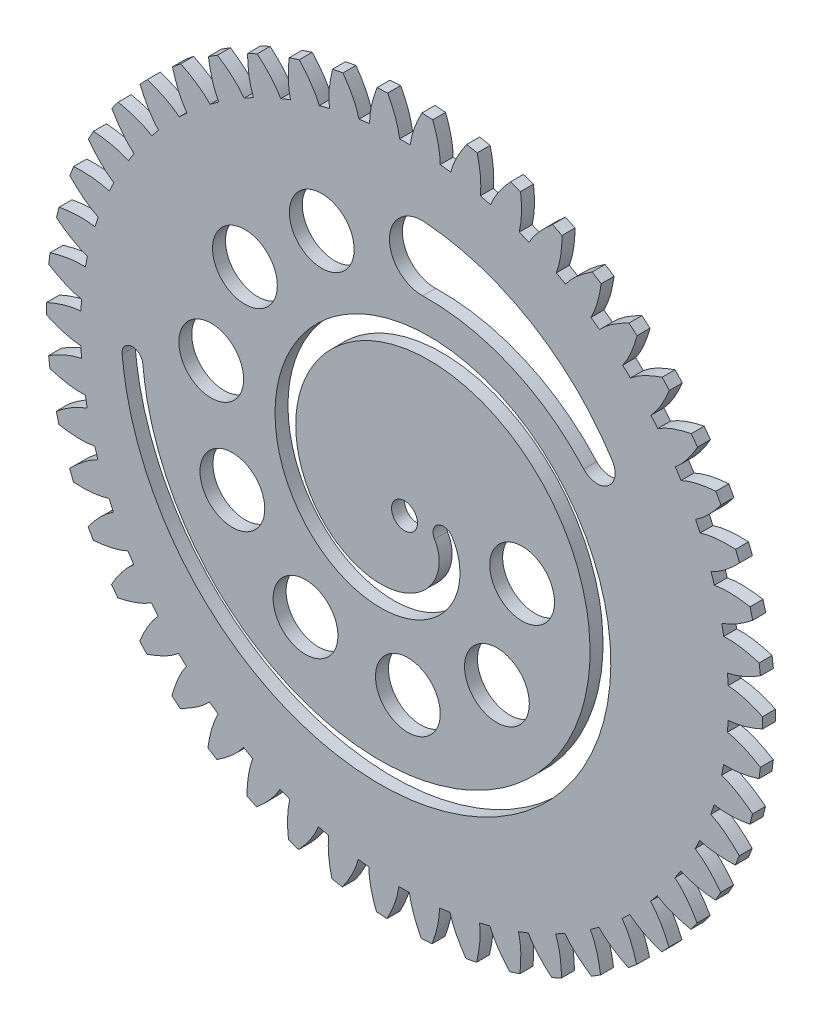
SolidWorks part; units mm, degrees
ref_plane "Front Plane" through (0, 0, 0) normal (0, 0, 1) x (1, 0, 0)
ref_plane "Top Plane" through (0, 0, 0) normal (0, 1, 0) x (1, 0, 0)
ref_plane "Right Plane" through (0, 0, 0) normal (1, 0, 0) x (0, 0, -1)
curve "spiralPointCurve"
  spline degree 3 poles (19.05, 0, 0) (19.4172, -0.6253, 0) (20.1672, -1.9024, 0) (21.0079, -4.0149, 0) (21.6393, -6.2921, 0) (22.0133, -8.7233, 0) (22.1141, -11.2761, 0) (21.9202, -13.9209, 0) (21.4165, -16.6238, 0) (20.5907, -19.3491, 0) (19.4346, -22.0596, 0) (17.9445, -24.7166, 0) (16.1209, -27.2807, 0) (13.9688, -29.7123, 0) (11.4979, -31.9717, 0) (8.7223, -34.0202, 0) (5.6607, -35.8203, 0) (2.3361, -37.3361, 0) (-1.2241, -38.534, 0) (-4.9887, -39.3831, 0) (-8.9227, -39.8555, 0) (-12.9877, -39.9272, 0) (-17.1422, -39.578, 0) (-21.3422, -38.7918, 0) (-25.5415, -37.5576, 0) (-29.6922, -35.8689, 0) (-33.7454, -33.7246, 0) (-37.6513, -31.1285, 0) (-41.3602, -28.0903, 0) (-44.8231, -24.6245, 0) (-47.992, -20.7514, 0) (-50.8203, -16.4964, 0) (-53.2642, -11.8901, 0) (-55.2822, -6.9681, 0) (-56.8365, -1.7705, 0) (-57.8932, 3.6581, 0) (-58.4224, 9.2692, 0) (-58.3993, 15.0108, 0) (-57.8043, 20.8278, 0) (-56.6233, 26.6626, 0) (-54.8479, 32.4557, 0) (-52.476, 38.1461, 0) (-49.5118, 43.6721, 0) (-45.9656, 48.9722, 0) (-41.8544, 53.985, 0) (-37.2014, 58.6506, 0) (-32.0364, 62.9111, 0) (-26.395, 66.711, 0) (-20.3191, 69.9981, 0) (-13.856, 72.7239, 0) (-7.0582, 74.8446, 0) (0.0167, 76.3213, 0) (7.3068, 77.1205, 0) (14.7466, 77.2149, 0) (22.267, 76.5835, 0) (29.7967, 75.2123, 0) (37.2623, 73.0942, 0) (44.589, 70.2296, 0) (51.7019, 66.6261, 0) (58.526, 62.2992, 0) (64.9877, 57.2718, 0) (71.0151, 51.5745, 0) (76.5387, 45.2451, 0) (81.4927, 38.3287, 0) (85.815, 30.8772, 0) (89.4486, 22.9489, 0) (92.3418, 14.6082, 0) (94.4491, 5.9251, 0) (95.7316, -3.0256, 0) (96.1576, -12.1648, 0) (95.7031, -21.4098, 0) (94.3521, -30.6749, 0) (92.0971, -39.8727, 0) (88.939, -48.9143, 0) (84.8878, -57.7105, 0) (79.9619, -66.1726, 0) (74.189, -74.2134, 0) (67.6053, -81.7478, 0) (60.2554, -88.694, 0) (52.1926, -94.9739, 0) (43.4777, -100.5147, 0) (34.1792, -105.2488, 0) (24.3724, -109.1154, 0) (14.139, -112.0603, 0) (3.5664, -114.0377, 0) (-7.2532, -115.0096, 0) (-18.2235, -114.9471, 0) (-29.2447, -113.8307, 0) (-40.2151, -111.6503, 0) (-51.0312, -108.4059, 0) (-61.5893, -104.1076, 0) (-71.7862, -98.7755, 0) (-81.5202, -92.4401, 0) (-90.6922, -85.1417, 0) (-99.2067, -76.9305, 0) (-106.9726, -67.8662, 0) (-113.9048, -58.0177, 0) (-119.9223, -47.4621, 0) (-124.9605, -36.2854, 0) (-128.9275, -24.5778, 0) (-131.8742, -12.448, 0) (-132.8567, -4.1612, 0) (-133.35, 0, 0) knots 0 0 0 0 0.002979 0.006084 0.009318 0.012682 0.016177 0.019804 0.023566 0.027462 0.031493 0.035662 0.039967 0.04441 0.048992 0.053713 0.058573 0.063573 0.068714 0.073995 0.079418 0.084982 0.090688 0.096536 0.102526 0.10866 0.114935 0.121354 0.127917 0.134623 0.141472 0.148465 0.155602 0.162884 0.170309 0.177879 0.185593 0.193453 0.201456 0.209605 0.217898 0.226337 0.234921 0.24365 0.252524 0.261543 0.270708 0.280019 0.289475 0.299076 0.308824 0.318717 0.328756 0.33894 0.349271 0.359748 0.37037 0.381139 0.392054 0.403114 0.414322 0.425675 0.437174 0.44882 0.460612 0.47255 0.484635 0.496866 0.509244 0.521768 0.534439 0.547256 0.560219 0.57333 0.586586 0.59999 0.61354 0.627237 0.64108 0.65507 0.669207 0.68349 0.697921 0.712498 0.727221 0.742092 0.75711 0.772274 0.787585 0.803043 0.818648 0.8344 0.850299 0.866344 0.882537 0.898876 0.915363 0.931996 0.948777 0.965704 0.982779 1 1 1 1
sketch "spiralSketch" plane through (0, 0, 0) normal (0, 0, 1) x (1, 0, 0)
  line L0 (30.4685, 172.8151) -> (35.6087, 171.8296)
  line L1 (8.5687, 175.2711) -> (13.7919, 174.9376)
  line L2 (51.8877, 167.6337) -> (56.8638, 166.0117)
  line L3 (72.4886, 159.8086) -> (77.2222, 157.5757)
  line L4 (91.9463, 149.4632) -> (96.3628, 146.6547)
  line L5 (109.954, 136.7607) -> (113.9836, 133.4208)
  line L6 (126.2277, 121.9014) -> (129.8069, 118.0828)
  line L7 (140.5106, 105.1197) -> (143.583, 100.8826)
  line L8 (152.5776, 86.6801) -> (155.0948, 82.0914)
  line L9 (162.2384, 66.8736) -> (164.1606, 62.0055)
  line L10 (169.3406, 46.0124) -> (170.6375, 40.9418)
  line L11 (173.7722, 24.4256) -> (174.4233, 19.2324)
  line L12 (175.4633, 2.4535) -> (175.4584, -2.7803)
  line L13 (174.3872, -19.5572) -> (173.7264, -24.7491)
  line L14 (170.5609, -41.2595) -> (169.2546, -46.3277)
  line L15 (164.0448, -62.3111) -> (162.1136, -67.1756)
  line L16 (154.9416, -82.38) -> (152.416, -86.9641)
  line L17 (143.3949, -101.1498) -> (140.3146, -105.3812)
  line L18 (129.5868, -118.3243) -> (126.0004, -122.1363)
  line L19 (113.735, -133.6328) -> (109.6992, -136.9652)
  line L20 (96.0895, -146.8339) -> (91.6679, -149.6342)
  line L21 (76.9287, -157.7193) -> (72.1909, -159.9433)
  line L22 (56.5546, -166.1173) -> (51.5754, -167.73)
  line L23 (35.2886, -171.8956) -> (30.1466, -172.8715)
  line L24 (13.4661, -174.963) -> (8.2423, -175.2868)
  line L25 (-8.5687, -175.2711) -> (-13.7919, -174.9376)
  line L26 (-30.4685, -172.8151) -> (-35.6087, -171.8296)
  line L27 (-51.8877, -167.6337) -> (-56.8638, -166.0117)
  line L28 (-72.4886, -159.8086) -> (-77.2222, -157.5757)
  line L29 (-91.9463, -149.4632) -> (-96.3628, -146.6547)
  line L30 (-109.954, -136.7607) -> (-113.9836, -133.4208)
  line L31 (-126.2277, -121.9014) -> (-129.8069, -118.0828)
  line L32 (-140.5106, -105.1197) -> (-143.583, -100.8826)
  line L33 (-152.5776, -86.6801) -> (-155.0948, -82.0914)
  line L34 (-162.2384, -66.8736) -> (-164.1606, -62.0055)
  line L35 (-169.3406, -46.0124) -> (-170.6375, -40.9418)
  line L36 (-173.7722, -24.4256) -> (-174.4233, -19.2324)
  line L37 (-175.4633, -2.4535) -> (-175.4584, 2.7803)
  line L38 (-174.3872, 19.5572) -> (-173.7264, 24.7491)
  line L39 (-170.5609, 41.2595) -> (-169.2546, 46.3277)
  line L40 (-164.0448, 62.3111) -> (-162.1136, 67.1756)
  line L41 (-154.9416, 82.38) -> (-152.416, 86.9641)
  line L42 (-143.3949, 101.1498) -> (-140.3146, 105.3812)
  line L43 (-129.5868, 118.3243) -> (-126.0004, 122.1363)
  line L44 (-113.735, 133.6328) -> (-109.6992, 136.9652)
  line L45 (-96.0895, 146.8339) -> (-91.6679, 149.6342)
  line L46 (-76.9287, 157.7193) -> (-72.1909, 159.9433)
  line L47 (-56.5546, 166.1173) -> (-51.5754, 167.73)
  line L48 (-35.2886, 171.8956) -> (-30.1466, 172.8715)
  line L49 (-13.4661, 174.963) -> (-8.2423, 175.2868)
  arc A0 (14.6695, -2.5724) -> (23.4305, 2.5724) centre (19.05, 0) cw
  arc A1 (-128.3053, 0.5981) -> (-138.3947, -0.5981) centre (-133.35, 0) ccw
  arc A2 (124.0747, 99.0305) -> (120.7741, 103.03) centre (0, 0) ccw
  arc A3 (135.5081, 82.6989) -> (132.7349, 87.0805) centre (0, 0) ccw
  arc A4 (144.8045, 65.0631) -> (142.6023, 69.7578) centre (0, 0) ccw
  arc A5 (151.8173, 46.4013) -> (150.2208, 51.3349) centre (0, 0) ccw
  arc A6 (156.4358, 27.0076) -> (155.4702, 32.1025) centre (0, 0) ccw
  arc A7 (158.5872, 7.1881) -> (158.2678, 12.3638) centre (0, 0) ccw
  arc A8 (155.3925, -32.4768) -> (156.3703, -27.3843) centre (0, 0) ccw
  arc A9 (158.2376, -12.7449) -> (158.5694, -7.5699) centre (0, 0) ccw
  arc A10 (150.0967, -51.6965) -> (151.7051, -46.7667) centre (0, 0) ccw
  arc A11 (142.4339, -70.101) -> (144.6474, -65.4117) centre (0, 0) ccw
  arc A12 (132.5248, -87.3999) -> (135.3086, -83.025) centre (0, 0) ccw
  arc A13 (120.5256, -103.3205) -> (123.8358, -99.329) centre (0, 0) ccw
  arc A14 (106.6258, -117.6117) -> (110.4101, -114.0665) centre (0, 0) ccw
  arc A15 (91.0443, -130.048) -> (95.2432, -127.0051) centre (0, 0) ccw
  arc A16 (74.0271, -140.4334) -> (78.5742, -137.9408) centre (0, 0) ccw
  arc A17 (55.8424, -148.6041) -> (60.6661, -146.701) centre (0, 0) ccw
  arc A18 (36.777, -154.4313) -> (41.8012, -153.1477) centre (0, 0) ccw
  arc A19 (17.1317, -157.8229) -> (22.2771, -157.1792) centre (0, 0) ccw
  arc A20 (-2.7839, -158.7256) -> (2.4016, -158.7318) centre (0, 0) ccw
  arc A21 (-22.6555, -157.1251) -> (-17.5117, -157.7812) centre (0, 0) ccw
  arc A22 (-42.1699, -153.0466) -> (-37.1488, -154.3422) centre (0, 0) ccw
  arc A23 (-61.0192, -146.5545) -> (-56.2001, -148.4692) centre (0, 0) ccw
  arc A24 (-78.9062, -137.7511) -> (-74.3651, -140.2548) centre (0, 0) ccw
  arc A25 (-95.5488, -126.7754) -> (-91.3573, -129.8284) centre (0, 0) ccw
  arc A26 (-110.6845, -113.8003) -> (-106.9087, -117.3546) centre (0, 0) ccw
  arc A27 (-124.0747, -99.0305) -> (-120.7741, -103.03) centre (0, 0) ccw
  arc A28 (-135.5081, -82.6989) -> (-132.7349, -87.0805) centre (0, 0) ccw
  arc A29 (-144.8045, -65.0631) -> (-142.6023, -69.7578) centre (0, 0) ccw
  arc A30 (-151.8173, -46.4013) -> (-150.2208, -51.3349) centre (0, 0) ccw
  arc A31 (-156.4358, -27.0076) -> (-155.4702, -32.1025) centre (0, 0) ccw
  arc A32 (-158.5872, -7.1881) -> (-158.2678, -12.3638) centre (0, 0) ccw
  arc A33 (-158.2376, 12.7449) -> (-158.5694, 7.5699) centre (0, 0) ccw
  arc A34 (-155.3925, 32.4768) -> (-156.3703, 27.3843) centre (0, 0) ccw
  arc A35 (-150.0967, 51.6965) -> (-151.7051, 46.7667) centre (0, 0) ccw
  arc A36 (-142.4339, 70.101) -> (-144.6474, 65.4117) centre (0, 0) ccw
  arc A37 (-132.5248, 87.3999) -> (-135.3086, 83.025) centre (0, 0) ccw
  arc A38 (-120.5256, 103.3205) -> (-123.8358, 99.329) centre (0, 0) ccw
  arc A39 (-106.6258, 117.6117) -> (-110.4101, 114.0665) centre (0, 0) ccw
  arc A40 (-91.0443, 130.048) -> (-95.2432, 127.0051) centre (0, 0) ccw
  arc A41 (-74.0271, 140.4334) -> (-78.5742, 137.9408) centre (0, 0) ccw
  arc A42 (-55.8424, 148.6041) -> (-60.6661, 146.701) centre (0, 0) ccw
  arc A43 (-36.777, 154.4313) -> (-41.8012, 153.1477) centre (0, 0) ccw
  arc A44 (-17.1317, 157.8229) -> (-22.2771, 157.1792) centre (0, 0) ccw
  arc A45 (2.7839, 158.7256) -> (-2.4016, 158.7318) centre (0, 0) ccw
  arc A46 (42.1699, 153.0466) -> (37.1488, 154.3422) centre (0, 0) ccw
  arc A47 (22.6555, 157.1251) -> (17.5117, 157.7812) centre (0, 0) ccw
  arc A48 (61.0192, 146.5545) -> (56.2001, 148.4692) centre (0, 0) ccw
  arc A49 (95.5488, 126.7754) -> (91.3573, 129.8284) centre (0, 0) ccw
  arc A50 (78.9062, 137.7511) -> (74.3651, 140.2548) centre (0, 0) ccw
  arc A51 (110.6845, 113.8003) -> (106.9087, 117.3546) centre (0, 0) ccw
  circle A52 centre (0, 0) radius 6.35
  spline S0 degree 3 poles (2653.0947, 1433.7434) (-78.7395, 11.3886) (9.9116, 23.866) (21.0079, -4.0149) (21.6393, -6.2921) (22.0133, -8.7233) (22.1141, -11.2761) (21.9202, -13.9209) (21.4165, -16.6238) (20.5907, -19.3491) (19.4346, -22.0596) (17.9445, -24.7166) (16.1209, -27.2807) (13.9688, -29.7123) (11.4979, -31.9717) (8.7223, -34.0202) (5.6607, -35.8203) (2.3361, -37.3361) (-1.2241, -38.534) (-4.9887, -39.3831) (-8.9227, -39.8555) (-12.9877, -39.9272) (-17.1422, -39.578) (-21.3422, -38.7918) (-25.5415, -37.5576) (-29.6922, -35.8689) (-33.7454, -33.7246) (-37.6513, -31.1285) (-41.3602, -28.0903) (-44.8231, -24.6245) (-47.992, -20.7514) (-50.8203, -16.4964) (-53.2642, -11.8901) (-55.2822, -6.9681) (-56.8365, -1.7705) (-57.8932, 3.6581) (-58.4224, 9.2692) (-58.3993, 15.0108) (-57.8043, 20.8278) (-56.6233, 26.6626) (-54.8479, 32.4557) (-52.476, 38.1461) (-49.5118, 43.6721) (-45.9656, 48.9722) (-41.8544, 53.985) (-37.2014, 58.6506) (-32.0364, 62.9111) (-26.395, 66.711) (-20.3191, 69.9981) (-13.856, 72.7239) (-7.0582, 74.8446) (0.0167, 76.3213) (7.3068, 77.1205) (14.7466, 77.2149) (22.267, 76.5835) (29.7967, 75.2123) (37.2623, 73.0942) (44.589, 70.2296) (51.7019, 66.6261) (58.526, 62.2992) (64.9877, 57.2718) (71.0151, 51.5745) (76.5387, 45.2451) (81.4927, 38.3287) (85.815, 30.8772) (89.4486, 22.9489) (92.3418, 14.6082) (94.4491, 5.9251) (95.7316, -3.0256) (96.1576, -12.1648) (95.7031, -21.4098) (94.3521, -30.6749) (92.0971, -39.8727) (88.939, -48.9143) (84.8878, -57.7105) (79.9619, -66.1726) (74.189, -74.2134) (67.6053, -81.7478) (60.2554, -88.694) (52.1926, -94.9739) (43.4777, -100.5147) (34.1792, -105.2488) (24.3724, -109.1154) (14.139, -112.0603) (3.5664, -114.0377) (-7.2532, -115.0096) (-18.2235, -114.9471) (-29.2447, -113.8307) (-40.2151, -111.6503) (-51.0312, -108.4059) (-61.5893, -104.1076) (-71.7862, -98.7755) (-81.5202, -92.4401) (-90.6922, -85.1417) (-99.2067, -76.9305) (-106.9726, -67.8662) (-113.9048, -58.0177) (-119.9223, -47.4621) (-124.9605, -36.2854) (-128.9275, -24.5778) (-154.4385, 80.4349) (-25.7709, 207.0314) (-3117.8887, -208.5982) knots -0.113657 -0.113657 -0.113657 -0.113657 0.002979 0.006084 0.009318 0.012682 0.016177 0.019804 0.023566 0.027462 0.031493 0.035662 0.039967 0.04441 0.048992 0.053713 0.058573 0.063573 0.068714 0.073995 0.079418 0.084982 0.090688 0.096536 0.102526 0.10866 0.114935 0.121354 0.127917 0.134623 0.141472 0.148465 0.155602 0.162884 0.170309 0.177879 0.185593 0.193453 0.201456 0.209605 0.217898 0.226337 0.234921 0.24365 0.252524 0.261543 0.270708 0.280019 0.289475 0.299076 0.308824 0.318717 0.328756 0.33894 0.349271 0.359748 0.37037 0.381139 0.392054 0.403114 0.414322 0.425675 0.437174 0.44882 0.460612 0.47255 0.484635 0.496866 0.509244 0.521768 0.534439 0.547256 0.560219 0.57333 0.586586 0.59999 0.61354 0.627237 0.64108 0.65507 0.669207 0.68349 0.697921 0.712498 0.727221 0.742092 0.75711 0.772274 0.787585 0.803043 0.818648 0.8344 0.850299 0.866344 0.882537 0.898876 0.915363 0.931996 0.948777 0.965704 0.982779 1.392238 1.392238 1.392238 1.392238 only from (19.05, 0) to (-133.35, 0) construction
  spline S1 degree 3 poles (19.05, 0) (19.4172, -0.6253) (20.1672, -1.9024) (21.0079, -4.0149) (21.6393, -6.2921) (22.0133, -8.7233) (22.1141, -11.2761) (21.9202, -13.9209) (21.4165, -16.6238) (20.5907, -19.3491) (19.4346, -22.0596) (17.9445, -24.7166) (16.1209, -27.2807) (13.9688, -29.7123) (11.4979, -31.9717) (8.7223, -34.0202) (5.6607, -35.8203) (2.3361, -37.3361) (-1.2241, -38.534) (-4.9887, -39.3831) (-8.9227, -39.8555) (-12.9877, -39.9272) (-17.1422, -39.578) (-21.3422, -38.7918) (-25.5415, -37.5576) (-29.6922, -35.8689) (-33.7454, -33.7246) (-37.6513, -31.1285) (-41.3602, -28.0903) (-44.8231, -24.6245) (-47.992, -20.7514) (-50.8203, -16.4964) (-53.2642, -11.8901) (-55.2822, -6.9681) (-56.8365, -1.7705) (-57.8932, 3.6581) (-58.4224, 9.2692) (-58.3993, 15.0108) (-57.8043, 20.8278) (-56.6233, 26.6626) (-54.8479, 32.4557) (-52.476, 38.1461) (-49.5118, 43.6721) (-45.9656, 48.9722) (-41.8544, 53.985) (-37.2014, 58.6506) (-32.0364, 62.9111) (-26.395, 66.711) (-20.3191, 69.9981) (-13.856, 72.7239) (-7.0582, 74.8446) (0.0167, 76.3213) (7.3068, 77.1205) (14.7466, 77.2149) (22.267, 76.5835) (29.7967, 75.2123) (37.2623, 73.0942) (44.589, 70.2296) (51.7019, 66.6261) (58.526, 62.2992) (64.9877, 57.2718) (71.0151, 51.5745) (76.5387, 45.2451) (81.4927, 38.3287) (85.815, 30.8772) (89.4486, 22.9489) (92.3418, 14.6082) (94.4491, 5.9251) (95.7316, -3.0256) (96.1576, -12.1648) (95.7031, -21.4098) (94.3521, -30.6749) (92.0971, -39.8727) (88.939, -48.9143) (84.8878, -57.7105) (79.9619, -66.1726) (74.189, -74.2134) (67.6053, -81.7478) (60.2554, -88.694) (52.1926, -94.9739) (43.4777, -100.5147) (34.1792, -105.2488) (24.3724, -109.1154) (14.139, -112.0603) (3.5664, -114.0377) (-7.2532, -115.0096) (-18.2235, -114.9471) (-29.2447, -113.8307) (-40.2151, -111.6503) (-51.0312, -108.4059) (-61.5893, -104.1076) (-71.7862, -98.7755) (-81.5202, -92.4401) (-90.6922, -85.1417) (-99.2067, -76.9305) (-106.9726, -67.8662) (-113.9048, -58.0177) (-119.9223, -47.4621) (-124.9605, -36.2854) (-128.9275, -24.5778) (-131.8742, -12.448) (-132.8567, -4.1612) (-133.35, 0) knots 0 0 0 0 0.002979 0.006084 0.009318 0.012682 0.016177 0.019804 0.023566 0.027462 0.031493 0.035662 0.039967 0.04441 0.048992 0.053713 0.058573 0.063573 0.068714 0.073995 0.079418 0.084982 0.090688 0.096536 0.102526 0.10866 0.114935 0.121354 0.127917 0.134623 0.141472 0.148465 0.155602 0.162884 0.170309 0.177879 0.185593 0.193453 0.201456 0.209605 0.217898 0.226337 0.234921 0.24365 0.252524 0.261543 0.270708 0.280019 0.289475 0.299076 0.308824 0.318717 0.328756 0.33894 0.349271 0.359748 0.37037 0.381139 0.392054 0.403114 0.414322 0.425675 0.437174 0.44882 0.460612 0.47255 0.484635 0.496866 0.509244 0.521768 0.534439 0.547256 0.560219 0.57333 0.586586 0.59999 0.61354 0.627237 0.64108 0.65507 0.669207 0.68349 0.697921 0.712498 0.727221 0.742092 0.75711 0.772274 0.787585 0.803043 0.818648 0.8344 0.850299 0.866344 0.882537 0.898876 0.915363 0.931996 0.948777 0.965704 0.982779 1 1 1 1
  spline S2 degree 1 poles (14.6695, -2.5724) (-128.3053, 0.5981) knots 0 0 1 1 construction
  spline S3 degree 3 poles (14.6695, -2.5724) (14.783, -2.7657) (15.0196, -3.1687) (15.4039, -3.8499) (15.7369, -4.5211) (16.1138, -5.4938) (16.5454, -6.8882) (16.8916, -8.6328) (17.0828, -11.5826) (16.6261, -15.3295) (14.5308, -21.1528) (9.6523, -27.54) (1.3225, -32.7622) (-8.3625, -35.1326) (-18.4292, -34.6118) (-28.0753, -31.4019) (-39.5555, -24.0029) (-50.1006, -9.978) (-53.9049, 7.245) (-52.838, 21.1681) (-49.1768, 34.6924) (-40.0818, 49.9801) (-23.6091, 63.6622) (-3.6002, 71.4558) (17.8788, 72.8707) (38.9025, 68.039) (57.8139, 57.5753) (73.2964, 42.441) (84.4036, 23.8169) (90.56, 2.9923) (91.5383, -18.73) (87.4213, -40.1076) (78.5554, -60.0178) (65.4988, -77.4974) (48.9689, -91.7694) (29.7906, -102.257) (8.8486, -108.5853) (-12.9555, -110.5755) (-34.7411, -108.2321) (-55.6799, -101.7241) (-75.0214, -91.3636) (-92.1125, -77.5804) (-106.4086, -60.9023) (-115.6463, -45.0745) (-120.5656, -33.2807) (-122.9243, -26.3624) (-124.483, -21.0878) (-125.8109, -15.7765) (-126.8561, -10.4675) (-127.6367, -5.0346) (-128.0841, -1.2684) (-128.3053, 0.5981) knots 0 0 0 0 0.000977 0.001953 0.003906 0.005859 0.007812 0.011719 0.015625 0.023438 0.03125 0.046875 0.0625 0.078125 0.09375 0.109375 0.125 0.15625 0.1875 0.203125 0.21875 0.25 0.28125 0.3125 0.34375 0.375 0.40625 0.4375 0.46875 0.5 0.53125 0.5625 0.59375 0.625 0.65625 0.6875 0.71875 0.75 0.78125 0.8125 0.84375 0.875 0.90625 0.9375 0.953125 0.960938 0.96875 0.976562 0.984375 0.992188 1 1 1 1
  spline S4 degree 1 poles (23.4305, 2.5724) (-138.3947, -0.5981) knots 0 0 1 1 construction
  spline S5 degree 3 poles (23.4305, 2.5724) (23.5577, 2.3558) (23.8025, 1.9386) (24.3554, 0.9671) (25.0794, -0.4876) (25.7259, -2.1818) (26.42, -4.4206) (27.0011, -7.3458) (27.2934, -12) (26.5831, -17.7492) (23.4796, -26.3115) (16.5681, -35.2761) (5.2825, -42.3063) (-7.4459, -45.396) (-20.3757, -44.709) (-32.5432, -40.6462) (-46.8114, -31.4326) (-59.6477, -14.2768) (-65.0885, 10.5243) (-60.7184, 35.2957) (-47.9282, 56.7401) (-28.8259, 72.586) (-5.8097, 81.5355) (18.7278, 83.1405) (42.603, 77.6437) (63.9679, 65.8134) (81.3776, 48.7854) (93.8147, 27.9197) (100.6809, 4.6759) (101.7644, -19.4867) (97.1949, -43.1926) (87.3874, -65.208) (72.9841, -84.485) (54.7943, -100.1863) (33.7385, -111.6975) (10.7952, -118.628) (-13.0455, -120.8018) (-36.8218, -118.2422) (-59.6341, -111.1499) (-80.6716, -99.8786) (-99.2319, -84.9093) (-114.7364, -66.8168) (-124.7333, -49.6898) (-130.0644, -36.9078) (-132.6109, -29.4369) (-134.2851, -23.7711) (-135.7264, -18.014) (-136.8826, -12.1386) (-137.7193, -6.2919) (-138.1684, -2.5063) (-138.3947, -0.5981) knots 0 0 0 0 0.000977 0.001953 0.003906 0.005859 0.007812 0.011719 0.015625 0.023438 0.03125 0.046875 0.0625 0.078125 0.09375 0.109375 0.125 0.15625 0.1875 0.21875 0.25 0.28125 0.3125 0.34375 0.375 0.40625 0.4375 0.46875 0.5 0.53125 0.5625 0.59375 0.625 0.65625 0.6875 0.71875 0.75 0.78125 0.8125 0.84375 0.875 0.90625 0.9375 0.953125 0.960938 0.96875 0.976562 0.984375 0.992188 1 1 1 1
  spline S6 degree 3 poles (37.1488, 154.3422) (37.8319, 160.2093) (36.9788, 166.1292) (35.6087, 171.8296) knots 0 0 0 0 1 1 1 1
  spline S7 degree 3 poles (22.6555, 157.1251) (24.0894, 162.8561) (27.1178, 168.018) (30.4685, 172.8151) knots 0 0 0 0 1 1 1 1
  spline S8 degree 3 poles (2.7839, 158.7256) (3.4881, 164.5911) (5.8457, 170.0919) (8.5687, 175.2711) knots 0 0 0 0 1 1 1 1
  spline S9 degree 3 poles (17.5117, 157.7812) (17.4541, 163.6876) (15.8657, 169.4539) (13.7919, 174.9376) knots 0 0 0 0 1 1 1 1
  spline S10 degree 3 poles (56.2001, 148.4692) (57.6132, 154.2044) (57.5087, 160.1845) (56.8638, 166.0117) knots 0 0 0 0 1 1 1 1
  spline S11 degree 3 poles (42.1699, 153.0466) (44.3107, 158.5527) (47.9622, 163.2944) (51.8877, 167.6337) knots 0 0 0 0 1 1 1 1
  spline S12 degree 3 poles (74.3651, 140.2548) (76.4858, 145.7676) (77.1317, 151.7136) (77.2222, 157.5757) knots 0 0 0 0 1 1 1 1
  spline S13 degree 3 poles (61.0192, 146.5545) (63.8332, 151.7489) (68.0502, 155.9955) (72.4886, 159.8086) knots 0 0 0 0 1 1 1 1
  spline S14 degree 3 poles (91.3573, 129.8284) (94.1522, 135.032) (95.5383, 140.8502) (96.3628, 146.6547) knots 0 0 0 0 1 1 1 1
  spline S15 degree 3 poles (78.9062, 137.7511) (82.349, 142.5519) (87.065, 146.2365) (91.9463, 149.4632) knots 0 0 0 0 1 1 1 1
  spline S16 degree 3 poles (106.9087, 117.3546) (110.3338, 122.1668) (112.4381, 127.7654) (113.9836, 133.4208) knots 0 0 0 0 1 1 1 1
  spline S17 degree 3 poles (95.5488, 126.7754) (99.5662, 131.1067) (104.7068, 134.1712) (109.954, 136.7607) knots 0 0 0 0 1 1 1 1
  spline S18 degree 3 poles (120.7741, 103.03) (124.7753, 107.375) (127.5648, 112.6657) (129.8069, 118.0828) knots 0 0 0 0 1 1 1 1
  spline S19 degree 3 poles (110.6845, 113.8003) (115.2131, 117.594) (120.6972, 119.99) (126.2277, 121.9014) knots 0 0 0 0 1 1 1 1
  spline S20 degree 3 poles (132.7349, 87.0805) (137.2491, 90.8898) (140.6796, 95.7892) (143.583, 100.8826) knots 0 0 0 0 1 1 1 1
  spline S21 degree 3 poles (124.0747, 99.0305) (129.0431, 102.2267) (134.7842, 103.9165) (140.5106, 105.1197) knots 0 0 0 0 1 1 1 1
  spline S22 degree 3 poles (142.6023, 69.7578) (147.5584, 72.9712) (151.5759, 77.402) (155.0948, 82.0914) knots 0 0 0 0 1 1 1 1
  spline S23 degree 3 poles (135.5081, 82.6989) (140.8379, 85.2472) (146.7456, 86.2041) (152.5776, 86.6801) knots 0 0 0 0 1 1 1 1
  spline S24 degree 3 poles (150.2208, 51.3349) (155.5406, 53.9019) (160.0817, 57.7942) (164.1606, 62.0055) knots 0 0 0 0 1 1 1 1
  spline S25 degree 3 poles (144.8045, 65.0631) (150.4117, 66.9233) (156.3927, 67.1322) (162.2384, 66.8736) knots 0 0 0 0 1 1 1 1
  spline S26 degree 3 poles (155.4702, 32.1025) (161.0698, 33.9824) (166.063, 37.2749) (170.6375, 40.9418) knots 0 0 0 0 1 1 1 1
  spline S27 degree 3 poles (151.8173, 46.4013) (157.6133, 47.544) (163.5734, 47.0017) (169.3406, 46.0124) knots 0 0 0 0 1 1 1 1
  spline S28 degree 3 poles (158.2678, 12.3638) (164.0588, 13.5271) (169.4253, 16.1678) (174.4233, 19.2324) knots 0 0 0 0 1 1 1 1
  spline S29 degree 3 poles (156.4358, 27.0076) (162.3294, 27.415) (168.1745, 26.1299) (173.7722, 24.4256) knots 0 0 0 0 1 1 1 1
  spline S30 degree 3 poles (158.5694, -7.5699) (164.4606, -7.1416) (170.1157, -5.1943) (175.4584, -2.7803) knots 0 0 0 0 1 1 1 1
  spline S31 degree 3 poles (158.5872, 7.1881) (164.4854, 6.8535) (170.1233, 4.846) (175.4633, 2.4535) knots 0 0 0 0 1 1 1 1
  spline S32 degree 3 poles (156.3703, -27.3843) (162.2687, -27.6977) (168.1233, -26.4745) (173.7264, -24.7491) knots 0 0 0 0 1 1 1 1
  spline S33 degree 3 poles (158.2376, -12.7449) (164.0473, -13.816) (169.3892, -16.5143) (174.3872, -19.5572) knots 0 0 0 0 1 1 1 1
  spline S34 degree 3 poles (151.7051, -46.7667) (157.5177, -47.8169) (163.4794, -47.3372) (169.2546, -46.3277) knots 0 0 0 0 1 1 1 1
  spline S35 degree 3 poles (155.3925, -32.4768) (161.0221, -34.2676) (165.9837, -37.6142) (170.5609, -41.2595) knots 0 0 0 0 1 1 1 1
  spline S36 degree 3 poles (144.6474, -65.4117) (150.2826, -67.1821) (156.2574, -67.4533) (162.1136, -67.1756) knots 0 0 0 0 1 1 1 1
  spline S37 degree 3 poles (150.0967, -51.6965) (155.4576, -54.1789) (159.9606, -58.1209) (164.0448, -62.3111) knots 0 0 0 0 1 1 1 1
  spline S38 degree 3 poles (135.3086, -83.025) (140.6774, -85.4877) (146.5711, -86.5057) (152.416, -86.9641) knots 0 0 0 0 1 1 1 1
  spline S39 degree 3 poles (142.4339, -70.101) (147.4413, -73.2356) (151.4148, -77.7109) (154.9416, -82.38) knots 0 0 0 0 1 1 1 1
  spline S40 degree 3 poles (123.8358, -99.329) (128.8537, -102.4452) (134.5733, -104.1938) (140.3146, -105.3812) knots 0 0 0 0 1 1 1 1
  spline S41 degree 3 poles (132.5248, -87.3999) (137.0998, -91.1375) (140.481, -96.0755) (143.3949, -101.1498) knots 0 0 0 0 1 1 1 1
  spline S42 degree 3 poles (110.4101, -114.0665) (114.9978, -117.787) (120.4532, -120.2387) (126.0004, -122.1363) knots 0 0 0 0 1 1 1 1
  spline S43 degree 3 poles (120.5256, -103.3205) (124.5962, -107.602) (127.3319, -112.9248) (129.5868, -118.3243) knots 0 0 0 0 1 1 1 1
  spline S44 degree 3 poles (95.2432, -127.0051) (99.3284, -131.2713) (104.4335, -134.3874) (109.6992, -136.9652) knots 0 0 0 0 1 1 1 1
  spline S45 degree 3 poles (106.6258, -117.6117) (110.1276, -122.3696) (112.1746, -127.9933) (113.735, -133.6328) knots 0 0 0 0 1 1 1 1
  spline S46 degree 3 poles (78.5742, -137.9408) (82.0925, -142.6853) (86.7668, -146.4167) (91.6679, -149.6342) knots 0 0 0 0 1 1 1 1
  spline S47 degree 3 poles (91.0443, -130.048) (93.9223, -135.2073) (95.2482, -141.0432) (96.0895, -146.8339) knots 0 0 0 0 1 1 1 1
  spline S48 degree 3 poles (60.6661, -146.701) (63.562, -151.8491) (67.7318, -156.1369) (72.1909, -159.9433) knots 0 0 0 0 1 1 1 1
  spline S49 degree 3 poles (74.0271, -140.4334) (76.2357, -145.9127) (76.8198, -151.8688) (76.9287, -157.7193) knots 0 0 0 0 1 1 1 1
  spline S50 degree 3 poles (41.8012, -153.1477) (44.029, -158.6182) (47.6286, -163.3948) (51.5754, -167.73) knots 0 0 0 0 1 1 1 1
  spline S51 degree 3 poles (55.8424, -148.6041) (57.3469, -154.317) (57.1798, -160.2994) (56.5546, -166.1173) knots 0 0 0 0 1 1 1 1
  spline S52 degree 3 poles (22.2771, -157.1792) (23.8017, -162.8857) (26.7742, -168.0758) (30.1466, -172.8715) knots 0 0 0 0 1 1 1 1
  spline S53 degree 3 poles (36.777, -154.4313) (37.5536, -160.2877) (36.6381, -166.2019) (35.2886, -171.8956) knots 0 0 0 0 1 1 1 1
  spline S54 degree 3 poles (2.4016, -158.7318) (3.1991, -164.5844) (5.4976, -170.1062) (8.2423, -175.2868) knots 0 0 0 0 1 1 1 1
  spline S55 degree 3 poles (17.1317, -157.8229) (17.1681, -163.7304) (15.5186, -169.4833) (13.4661, -174.963) knots 0 0 0 0 1 1 1 1
  spline S56 degree 3 poles (-17.5117, -157.7812) (-17.4541, -163.6876) (-15.8657, -169.4539) (-13.7919, -174.9376) knots 0 0 0 0 1 1 1 1
  spline S57 degree 3 poles (-2.7839, -158.7256) (-3.4881, -164.5911) (-5.8457, -170.0919) (-8.5687, -175.2711) knots 0 0 0 0 1 1 1 1
  spline S58 degree 3 poles (-37.1488, -154.3422) (-37.8319, -160.2093) (-36.9788, -166.1292) (-35.6087, -171.8296) knots 0 0 0 0 1 1 1 1
  spline S59 degree 3 poles (-22.6555, -157.1251) (-24.0894, -162.8561) (-27.1178, -168.018) (-30.4685, -172.8151) knots 0 0 0 0 1 1 1 1
  spline S60 degree 3 poles (-56.2001, -148.4692) (-57.6132, -154.2044) (-57.5087, -160.1845) (-56.8638, -166.0117) knots 0 0 0 0 1 1 1 1
  spline S61 degree 3 poles (-42.1699, -153.0466) (-44.3107, -158.5527) (-47.9622, -163.2944) (-51.8877, -167.6337) knots 0 0 0 0 1 1 1 1
  spline S62 degree 3 poles (-74.3651, -140.2548) (-76.4858, -145.7676) (-77.1317, -151.7136) (-77.2222, -157.5757) knots 0 0 0 0 1 1 1 1
  spline S63 degree 3 poles (-61.0192, -146.5545) (-63.8332, -151.7489) (-68.0502, -155.9955) (-72.4886, -159.8086) knots 0 0 0 0 1 1 1 1
  spline S64 degree 3 poles (-91.3573, -129.8284) (-94.1522, -135.032) (-95.5383, -140.8502) (-96.3628, -146.6547) knots 0 0 0 0 1 1 1 1
  spline S65 degree 3 poles (-78.9062, -137.7511) (-82.349, -142.5519) (-87.065, -146.2365) (-91.9463, -149.4632) knots 0 0 0 0 1 1 1 1
  spline S66 degree 3 poles (-106.9087, -117.3546) (-110.3338, -122.1668) (-112.4381, -127.7654) (-113.9836, -133.4208) knots 0 0 0 0 1 1 1 1
  spline S67 degree 3 poles (-95.5488, -126.7754) (-99.5662, -131.1067) (-104.7068, -134.1712) (-109.954, -136.7607) knots 0 0 0 0 1 1 1 1
  spline S68 degree 3 poles (-120.7741, -103.03) (-124.7753, -107.375) (-127.5648, -112.6657) (-129.8069, -118.0828) knots 0 0 0 0 1 1 1 1
  spline S69 degree 3 poles (-110.6845, -113.8003) (-115.2131, -117.594) (-120.6972, -119.99) (-126.2277, -121.9014) knots 0 0 0 0 1 1 1 1
  spline S70 degree 3 poles (-132.7349, -87.0805) (-137.2491, -90.8898) (-140.6796, -95.7892) (-143.583, -100.8826) knots 0 0 0 0 1 1 1 1
  spline S71 degree 3 poles (-124.0747, -99.0305) (-129.0431, -102.2267) (-134.7842, -103.9165) (-140.5106, -105.1197) knots 0 0 0 0 1 1 1 1
  spline S72 degree 3 poles (-142.6023, -69.7578) (-147.5584, -72.9712) (-151.5759, -77.402) (-155.0948, -82.0914) knots 0 0 0 0 1 1 1 1
  spline S73 degree 3 poles (-135.5081, -82.6989) (-140.8379, -85.2472) (-146.7456, -86.2041) (-152.5776, -86.6801) knots 0 0 0 0 1 1 1 1
  spline S74 degree 3 poles (-150.2208, -51.3349) (-155.5406, -53.9019) (-160.0817, -57.7942) (-164.1606, -62.0055) knots 0 0 0 0 1 1 1 1
  spline S75 degree 3 poles (-144.8045, -65.0631) (-150.4117, -66.9233) (-156.3927, -67.1322) (-162.2384, -66.8736) knots 0 0 0 0 1 1 1 1
  spline S76 degree 3 poles (-155.4702, -32.1025) (-161.0698, -33.9824) (-166.063, -37.2749) (-170.6375, -40.9418) knots 0 0 0 0 1 1 1 1
  spline S77 degree 3 poles (-151.8173, -46.4013) (-157.6133, -47.544) (-163.5734, -47.0017) (-169.3406, -46.0124) knots 0 0 0 0 1 1 1 1
  spline S78 degree 3 poles (-158.2678, -12.3638) (-164.0588, -13.5271) (-169.4253, -16.1678) (-174.4233, -19.2324) knots 0 0 0 0 1 1 1 1
  spline S79 degree 3 poles (-156.4358, -27.0076) (-162.3294, -27.415) (-168.1745, -26.1299) (-173.7722, -24.4256) knots 0 0 0 0 1 1 1 1
  spline S80 degree 3 poles (-158.5694, 7.5699) (-164.4606, 7.1416) (-170.1157, 5.1943) (-175.4584, 2.7803) knots 0 0 0 0 1 1 1 1
  spline S81 degree 3 poles (-158.5872, -7.1881) (-164.4854, -6.8535) (-170.1233, -4.846) (-175.4633, -2.4535) knots 0 0 0 0 1 1 1 1
  spline S82 degree 3 poles (-156.3703, 27.3843) (-162.2687, 27.6977) (-168.1233, 26.4745) (-173.7264, 24.7491) knots 0 0 0 0 1 1 1 1
  spline S83 degree 3 poles (-158.2376, 12.7449) (-164.0473, 13.816) (-169.3892, 16.5143) (-174.3872, 19.5572) knots 0 0 0 0 1 1 1 1
  spline S84 degree 3 poles (-151.7051, 46.7667) (-157.5177, 47.8169) (-163.4794, 47.3372) (-169.2546, 46.3277) knots 0 0 0 0 1 1 1 1
  spline S85 degree 3 poles (-155.3925, 32.4768) (-161.0221, 34.2676) (-165.9837, 37.6142) (-170.5609, 41.2595) knots 0 0 0 0 1 1 1 1
  spline S86 degree 3 poles (-144.6474, 65.4117) (-150.2826, 67.1821) (-156.2574, 67.4533) (-162.1136, 67.1756) knots 0 0 0 0 1 1 1 1
  spline S87 degree 3 poles (-150.0967, 51.6965) (-155.4576, 54.1789) (-159.9606, 58.1209) (-164.0448, 62.3111) knots 0 0 0 0 1 1 1 1
  spline S88 degree 3 poles (-135.3086, 83.025) (-140.6774, 85.4877) (-146.5711, 86.5057) (-152.416, 86.9641) knots 0 0 0 0 1 1 1 1
  spline S89 degree 3 poles (-142.4339, 70.101) (-147.4413, 73.2356) (-151.4148, 77.7109) (-154.9416, 82.38) knots 0 0 0 0 1 1 1 1
  spline S90 degree 3 poles (-123.8358, 99.329) (-128.8537, 102.4452) (-134.5733, 104.1938) (-140.3146, 105.3812) knots 0 0 0 0 1 1 1 1
  spline S91 degree 3 poles (-132.5248, 87.3999) (-137.0998, 91.1375) (-140.481, 96.0755) (-143.3949, 101.1498) knots 0 0 0 0 1 1 1 1
  spline S92 degree 3 poles (-110.4101, 114.0665) (-114.9978, 117.787) (-120.4532, 120.2387) (-126.0004, 122.1363) knots 0 0 0 0 1 1 1 1
  spline S93 degree 3 poles (-120.5256, 103.3205) (-124.5962, 107.602) (-127.3319, 112.9248) (-129.5868, 118.3243) knots 0 0 0 0 1 1 1 1
  spline S94 degree 3 poles (-95.2432, 127.0051) (-99.3284, 131.2713) (-104.4335, 134.3874) (-109.6992, 136.9652) knots 0 0 0 0 1 1 1 1
  spline S95 degree 3 poles (-106.6258, 117.6117) (-110.1276, 122.3696) (-112.1746, 127.9933) (-113.735, 133.6328) knots 0 0 0 0 1 1 1 1
  spline S96 degree 3 poles (-78.5742, 137.9408) (-82.0925, 142.6853) (-86.7668, 146.4167) (-91.6679, 149.6342) knots 0 0 0 0 1 1 1 1
  spline S97 degree 3 poles (-91.0443, 130.048) (-93.9223, 135.2073) (-95.2482, 141.0432) (-96.0895, 146.8339) knots 0 0 0 0 1 1 1 1
  spline S98 degree 3 poles (-60.6661, 146.701) (-63.562, 151.8491) (-67.7318, 156.1369) (-72.1909, 159.9433) knots 0 0 0 0 1 1 1 1
  spline S99 degree 3 poles (-74.0271, 140.4334) (-76.2357, 145.9127) (-76.8198, 151.8688) (-76.9287, 157.7193) knots 0 0 0 0 1 1 1 1
  spline S100 degree 3 poles (-41.8012, 153.1477) (-44.029, 158.6182) (-47.6286, 163.3948) (-51.5754, 167.73) knots 0 0 0 0 1 1 1 1
  spline S101 degree 3 poles (-55.8424, 148.6041) (-57.3469, 154.317) (-57.1798, 160.2994) (-56.5546, 166.1173) knots 0 0 0 0 1 1 1 1
  spline S102 degree 3 poles (-22.2771, 157.1792) (-23.8017, 162.8857) (-26.7742, 168.0758) (-30.1466, 172.8715) knots 0 0 0 0 1 1 1 1
  spline S103 degree 3 poles (-36.777, 154.4313) (-37.5536, 160.2877) (-36.6381, 166.2019) (-35.2886, 171.8956) knots 0 0 0 0 1 1 1 1
  spline S104 degree 3 poles (-2.4016, 158.7318) (-3.1991, 164.5844) (-5.4976, 170.1062) (-8.2423, 175.2868) knots 0 0 0 0 1 1 1 1
  spline S105 degree 3 poles (-17.1317, 157.8229) (-17.1681, 163.7304) (-15.5186, 169.4833) (-13.4661, 174.963) knots 0 0 0 0 1 1 1 1
  point P211 (0, 0)
  dimension "D3" = 317.5
  dimension "D5" = 12.7
  dimension "D1" = 5.08
  dimension "D2" = 5.08
  dimension "D4" = 50
extrude "Boss-Extrude3" add sketch "spiralSketch" along normal blind 6.35 contours S105 A44 S102 L48 S103 A43 S100 L47 S101 A42 S98 L46 S99 A41 S96 L45 S97 A40 S94 L44 S95 A39 S92 L43 S93 A38 S90 L42 S91 A37 S88 L41 S89 A36 S86 L40 S87 A35 S84 L39 S85 A34 S82 L38 S83 A33 S80 L37 S81 A32 S78
sketch "Sketch1" plane through (0, 0, 6.35) normal (0, 0, 1) x (1, 0, 0)
  spline S8 degree 3 poles (3984.5038, -302.0261) (403.1381, -645.2673) (31.165, 52.2238) (51.3125, 17.2778) (51.5749, 16.8167) (52.1764, 15.7128) (52.5156, 15.07) (52.972, 14.1461) (53.0638, 13.9575) (53.2413, 13.5869) (53.5018, 13.0345) (53.7454, 12.4932) (54.5228, 10.7151) (55.0338, 9.3771) (55.5725, 7.8223) (55.6748, 7.5188) (55.8761, 6.9045) (56.171, 5.9788) (56.6261, 4.4144) (56.95, 3.1405) (57.2529, 1.8557) (57.3942, 1.2057) (57.7805, -0.7317) (57.9895, -2.0126) (58.3194, -4.5497) (58.4403, -5.8047) (58.602, -8.3032) (58.6425, -9.545) (58.6467, -12.0117) (58.6103, -13.2363) (58.4655, -15.6587) (58.3571, -16.8575) (57.9301, -20.4151) (57.5102, -22.7325) (55.8914, -29.5065) (54.3369, -33.7718) (50.4961, -41.7267) (48.2114, -45.4123) (43.0966, -52.1624) (40.2659, -55.227) (34.2177, -60.7187) (30.9977, -63.1481) (24.3008, -67.3772) (20.8237, -69.1774) (13.7221, -72.17) (10.0969, -73.3626) (2.796, -75.1687) (-0.8812, -75.7827) (-8.2085, -76.4684) (-11.8594, -76.5402) (-19.0673, -76.1819) (-22.6244, -75.7519) (-29.5882, -74.4338) (-32.9962, -73.5455) (-39.6173, -71.3549) (-42.83, -70.053) (-52.121, -65.5937) (-57.846, -61.8849) (-65.5725, -55.4878) (-68.0063, -53.2156) (-72.5707, -48.437) (-74.702, -45.9301) (-80.626, -38.1187) (-83.9448, -32.5275) (-89.2853, -20.8851) (-91.3058, -14.8377) (-94.0675, -2.5669) (-94.809, 3.6557) (-95.0751, 16.0283) (-94.6004, 22.1789) (-92.5303, 34.1983) (-90.9357, 40.0663) (-86.7445, 51.3498) (-84.1499, 56.7613) (-78.0924, 66.9948) (-74.6319, 71.8126) (-66.9896, 80.747) (-62.8069, 84.8645) (-53.8718, 92.3178) (-49.1174, 95.6559) (-39.1835, 101.5031) (-34.0056, 104.0119) (-23.3683, 108.1767) (-17.9086, 109.8325) (-6.8498, 112.2865) (-1.2493, 113.0852) (9.9676, 113.8414) (15.5817, 113.7988) (26.703, 112.9043) (32.2109, 112.0526) (43.0161, 109.5846) (48.3108, 107.969) (58.5906, 104.0314) (63.5765, 101.7092) (73.1572, 96.4233) (77.7514, 93.4599) (86.4767, 86.9657) (90.6085, 83.4343) (98.3512, 75.882) (101.9626, 71.8608) (108.6211, 63.4067) (111.6666, 58.976) (117.1584, 49.788) (119.605, 45.0298) (123.8757, 35.2706) (125.7002, 30.2691) (128.716, 20.1008) (129.9067, 14.9369) (131.6524, 4.5252) (132.2075, -0.7227) (132.6889, -11.2231) (132.6153, -16.4775) (131.8548, -26.9193) (131.168, -32.1067) (129.2031, -42.3503) (127.9257, -47.4036) (123.2506, -62.2703) (119.0085, -71.7846) (111.1829, -85.1312) (108.3305, -89.4279) (102.1838, -97.6679) (98.8888, -101.6121) (88.4099, -112.8577) (80.6326, -119.5677) (63.8936, -131.174) (54.9356, -136.0685) (36.2614, -143.8953) (26.5446, -146.8281) (6.7788, -150.6744) (-3.2739, -151.5891) (-23.3061, -151.4267) (-33.2901, -150.35) (-52.8112, -146.3057) (-62.3526, -143.3374) (-80.6564, -135.6721) (-89.4226, -130.9736) (-105.8919, -120.0596) (-113.5985, -113.8419) (-127.7177, -100.1389) (-134.1328, -92.6516) (-142.6549, -80.6747) (-145.3142, -76.5554) (-150.2455, -68.1121) (-152.5176, -63.7905) (-155.6365, -57.1615) (-156.6277, -54.9274) (-158.5108, -50.4133) (-159.403, -48.1306) (-161.075, -43.5591) (-162.2478, -40.1201) (-163.3045, -36.6714) (-163.8141, -34.9459) (-163.9807, -34.3711) (-164.3098, -33.2133) (-164.472, -32.6312) (-165.2704, -29.7049) (-165.869, -27.3126) (-166.6889, -23.646) (-167.0794, -21.7932) (-167.4371, -19.9111) (-167.6102, -18.9652) (-167.667, -18.6489) (-167.7772, -18.0225) (-167.8308, -17.7115) (-168.3016, -14.9319) (-168.634, -12.6009) (-183.8012, 103.0215) (-74.9947, -178.0263) (-3900.7368, -1437.0646) knots -0.089062 -0.089062 -0.089062 -0.089062 0.000977 0.000977 0.001953 0.001953 0.00293 0.00293 0.003174 0.003174 0.003418 0.003906 0.003906 0.005859 0.005859 0.006348 0.006348 0.006836 0.007813 0.008789 0.008789 0.009766 0.009766 0.011719 0.011719 0.013672 0.013672 0.015625 0.015625 0.017578 0.017578 0.019531 0.019531 0.023437 0.023437 0.03125 0.03125 0.039062 0.039062 0.046875 0.046875 0.054687 0.054687 0.0625 0.0625 0.070312 0.070312 0.078125 0.078125 0.085937 0.085937 0.09375 0.09375 0.101562 0.101562 0.109375 0.109375 0.125 0.125 0.132812 0.132812 0.140625 0.140625 0.15625 0.15625 0.171875 0.171875 0.1875 0.1875 0.203125 0.203125 0.21875 0.21875 0.234375 0.234375 0.25 0.25 0.265625 0.265625 0.28125 0.28125 0.296875 0.296875 0.3125 0.3125 0.328125 0.328125 0.34375 0.34375 0.359375 0.359375 0.375 0.375 0.390625 0.390625 0.40625 0.40625 0.421875 0.421875 0.4375 0.4375 0.453125 0.453125 0.46875 0.46875 0.484375 0.484375 0.5 0.5 0.515625 0.515625 0.53125 0.53125 0.546875 0.546875 0.5625 0.5625 0.59375 0.59375 0.609375 0.609375 0.625 0.625 0.65625 0.65625 0.6875 0.6875 0.71875 0.71875 0.75 0.75 0.78125 0.78125 0.8125 0.8125 0.84375 0.84375 0.875 0.875 0.90625 0.90625 0.921875 0.921875 0.9375 0.9375 0.945313 0.945313 0.953125 0.953125 0.960938 0.964844 0.964844 0.966797 0.966797 0.96875 0.96875 0.976563 0.976563 0.980469 0.982422 0.982422 0.983398 0.983398 0.984375 0.984375 0.992188 0.992188 1.39789 1.39789 1.39789 1.39789 only from (50.5897, 18.5216) to (-169.6716, -4.3061)
  spline S9 degree 3 poles (57.6317, 0) (57.84, -1.1021) (58.0134, -2.1961) (58.3194, -4.5497) (58.4403, -5.8047) (58.602, -8.3032) (58.6425, -9.545) (58.6467, -12.0117) (58.6103, -13.2363) (58.4655, -15.6587) (58.3571, -16.8575) (57.9301, -20.4151) (57.5102, -22.7325) (55.8914, -29.5065) (54.3369, -33.7718) (50.4961, -41.7267) (48.2114, -45.4123) (43.0966, -52.1624) (40.2659, -55.227) (34.2177, -60.7187) (30.9977, -63.1481) (24.3008, -67.3772) (20.8237, -69.1774) (13.7221, -72.17) (10.0969, -73.3626) (2.796, -75.1687) (-0.8812, -75.7827) (-8.2085, -76.4684) (-11.8594, -76.5402) (-19.0673, -76.1819) (-22.6244, -75.7519) (-29.5882, -74.4338) (-32.9962, -73.5455) (-39.6173, -71.3549) (-42.83, -70.053) (-52.121, -65.5937) (-57.846, -61.8849) (-65.5725, -55.4878) (-68.0063, -53.2156) (-72.5707, -48.437) (-74.702, -45.9301) (-80.626, -38.1187) (-83.9448, -32.5275) (-89.2853, -20.8851) (-91.3058, -14.8377) (-94.0675, -2.5669) (-94.809, 3.6557) (-95.0751, 16.0283) (-94.6004, 22.1789) (-92.5303, 34.1983) (-90.9357, 40.0663) (-86.7445, 51.3498) (-84.1499, 56.7613) (-78.0924, 66.9948) (-74.6319, 71.8126) (-66.9896, 80.747) (-62.8069, 84.8645) (-53.8718, 92.3178) (-49.1174, 95.6559) (-39.1835, 101.5031) (-34.0056, 104.0119) (-23.3683, 108.1767) (-17.9086, 109.8325) (-8.2832, 111.9684) (-4.1483, 112.6423) (0, 113.0843) knots 0.010048 0.010048 0.010048 0.010048 0.011719 0.011719 0.013672 0.013672 0.015625 0.015625 0.017578 0.017578 0.019531 0.019531 0.023437 0.023437 0.03125 0.03125 0.039062 0.039062 0.046875 0.046875 0.054687 0.054687 0.0625 0.0625 0.070312 0.070312 0.078125 0.078125 0.085937 0.085937 0.09375 0.09375 0.101562 0.101562 0.109375 0.109375 0.125 0.125 0.132812 0.132812 0.140625 0.140625 0.15625 0.15625 0.171875 0.171875 0.1875 0.1875 0.203125 0.203125 0.21875 0.21875 0.234375 0.234375 0.25 0.25 0.265625 0.265625 0.28125 0.28125 0.296875 0.296875 0.3125 0.3125 0.324074 0.324074 0.324074 0.324074 construction
  point P0 (45.2804, -49.2756)
  point P3 (8.5285, 113.6672)
  point P4 (1.6445, -75.2862)
  point P5 (-48.5184, -67.2659)
  point P6 (-84.3633, -31.2689)
  point P7 (-94.7366, 18.4607)
  point P8 (-78.2153, 66.4991)
  point P9 (58.3957, 103.9768)
  point P10 (99.6369, 74.3154)
  point P11 (125.4784, 30.5791)
  point P12 (132.3625, -19.7523)
  point P20 (-40.5621, 100.6001)
  dimension "D3" = 50.8
  dimension "D4" = 50.8
  dimension "D5" = 50.8
  dimension "D6" = 50.8
  dimension "D7" = 50.8
  dimension "D8" = 50.8
  dimension "D9" = 50.8
  dimension "D10" = 50.8
  dimension "D12" = 50.8
  dimension "D11" = 50.8
  dimension "D13" = 50.8
  dimension "D2" = 50.8
  dimension "D1" = 36.576
sketch "Sketch2" plane through (0, 0, 6.35) normal (0, 0, 1) x (1, 0, 0)
  line L0 (87.8232, 63.7111) -> (101.8203, 74.3154) construction
  line L1 (7.3407, 97.8366) -> (9.7214, 129.5659) construction
  circle A0 centre (57.6317, 0) radius 15.875
  circle A1 centre (45.2804, -49.2756) radius 15.875
  circle A2 centre (1.6445, -75.2862) radius 15.875
  circle A3 centre (-48.5184, -67.2659) radius 15.875
  circle A4 centre (-84.3633, -31.2689) radius 15.875
  circle A5 centre (-94.7366, 18.4607) radius 15.875
  circle A8 centre (-78.2153, 66.4991) radius 15.875
  circle A9 centre (-40.5621, 100.6001) radius 15.875
  circle A11 centre (58.3957, 103.9768) radius 15.875 construction
  arc A12 (8.5285, 113.6672) -> (99.6369, 74.3154) centre (11.3585, -4.9251) cw construction
  arc A13 (111.4507, 84.9196) -> (8.1498, 129.5376) centre (11.3585, -4.9251) ccw construction
  arc A14 (87.8232, 63.7111) -> (8.9072, 97.7967) centre (11.3585, -4.9251) ccw construction
  arc A15 (87.8232, 63.7111) -> (111.4507, 84.9196) centre (99.6369, 74.3154) ccw construction
  arc A16 (8.1498, 129.5376) -> (8.9072, 97.7967) centre (8.5285, 113.6672) ccw construction
  arc A18 (87.8232, 63.7111) -> (101.8203, 74.3154) centre (94.3798, 69.5965) ccw
  arc A19 (9.7214, 129.5659) -> (101.8203, 74.3154) centre (0.7404, 10.2088) cw
  arc A20 (8.9072, 97.7967) -> (87.8232, 63.7111) centre (11.3585, -4.9251) cw
  arc A21 (9.7214, 129.5659) -> (8.9072, 97.7967) centre (8.5277, 113.7015) ccw
  point P13 (8.5285, 113.6672)
  point P14 (-40.5621, 100.6001)
  point P15 (-78.2153, 66.4991)
  point P16 (58.3957, 103.9768)
  point P26 (58.3957, 103.9768)
  dimension "D1" = 31.75
extrude "Cut-Extrude1" cut sketch "Sketch2" against normal up to surface (6.35 mm away) up to face at (0, 0, 0)
equation "\"D1@spiralSketch\" = \"slotRadius@405TermProject.Assembly\""
equation "\"D3@spiralSketch\" = \"diskDiameter@405TermProject.Assembly\""
equation "\"D1@Boss-Extrude3\"=\"diskThickness@405TermProject.Assembly\""
equation "\"D3@Sketch1\"=\"spiralReliefSpacing@405TermProject.Assembly\""
equation "\"D4@Sketch1\"=\"spiralReliefSpacing@405TermProject.Assembly\""
equation "\"D5@Sketch1\"=\"spiralReliefSpacing@405TermProject.Assembly\""
equation "\"D6@Sketch1\"=\"spiralReliefSpacing@405TermProject.Assembly\""
equation "\"D7@Sketch1\"=\"spiralReliefSpacing@405TermProject.Assembly\""
equation "\"D1@Sketch2\"=\"spiralReliefDiameter@405TermProject.Assembly\""
equation "\"D8@Sketch1\"=\"spiralReliefSpacing@405TermProject.Assembly\""
equation "\"D9@Sketch1\"=\"spiralReliefSpacing@405TermProject.Assembly\""
equation "\"D10@Sketch1\"=\"spiralReliefSpacing@405TermProject.Assembly\""
equation "\"D12@Sketch1\"=\"spiralReliefSpacing@405TermProject.Assembly\""
equation "\"D11@Sketch1\"=\"spiralReliefSpacing@405TermProject.Assembly\""
equation "\"D13@Sketch1\"=\"spiralReliefSpacing@405TermProject.Assembly\""
equation "\"D2@Sketch1\"=\"spiralReliefSpacing@405TermProject.Assembly\""
